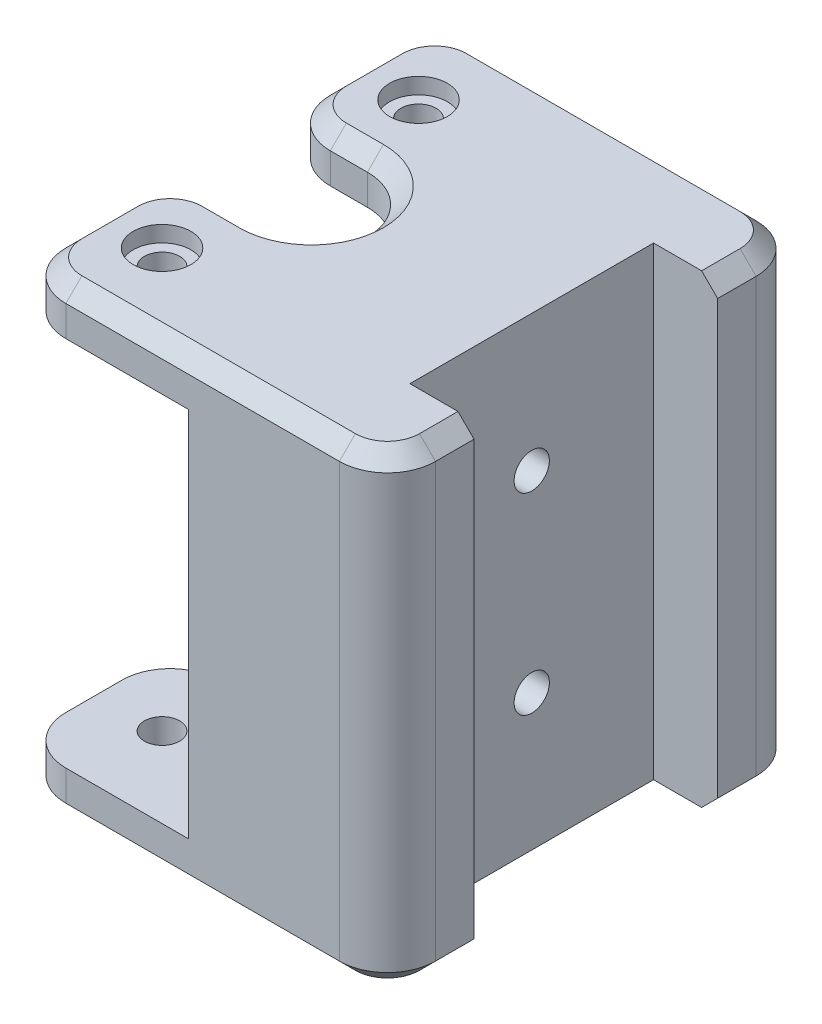
SolidWorks part; units mm, degrees
ref_plane "Спереди" through (0, 0, 0) normal (0, 0, 1) x (1, 0, 0)
ref_plane "Сверху" through (0, 0, 0) normal (0, 1, 0) x (1, 0, 0)
ref_plane "Справа" through (0, 0, 0) normal (1, 0, 0) x (0, 0, -1)
sketch "Эскиз2" plane through (0, 0, 0) normal (0, 1, 0) x (1, 0, 0)
  line L0 (23.6854, 8) -> (23.6854, -8) construction
  line L2 (19.6854, 13) -> (42.75, 13)
  line L3 (19.6854, 13) -> (19.6854, -13)
  line L4 (19.6854, -13) -> (42.75, -13)
  line L5 (42.75, 13) -> (42.75, -13)
  line L6 (19.6854, 13) -> (42.75, -13) construction
  line L7 (19.6854, -13) -> (42.75, 13) construction
  circle A0 centre (0, 0) radius 25 construction
  circle A1 centre (23.6854, 8) radius 1.1
  circle A2 centre (23.6854, -8) radius 1.1
  point P7 (31.2177, 0)
  dimension "D1" = 50
  dimension "D3" = 2.2
  dimension "D4" = 2.2
  dimension "D2" = 16
  dimension "D5" = 4
  dimension "D6" = 42.75
  dimension "D7" = 26
extrude "Бобышка-Вытянуть1" add sketch "Эскиз2" along normal mid plane 29
sketch "Эскиз3" plane through (0, 0, 0) normal (0, 1, 0) x (1, 0, 0)
  circle A0 centre (0, 0) radius 33
  dimension "D1" = 66
extrude "Вырез-Вытянуть1" cut sketch "Эскиз3" against normal mid plane 23.2
sketch "Эскиз4" plane through (0, 14.5, 0) normal (0, 1, 0) x (1, 0, 0)
  line L0 (25, 3.5) -> (19.6854, 3.5)
  line L1 (19.6854, 13) -> (19.6854, -13) construction
  line L2 (19.6854, 3.5) -> (19.6854, -3.5)
  line L3 (19.6854, -3.5) -> (25, -3.5)
  circle A0 centre (0, 0) radius 25 construction
  circle A1 centre (25, 0) radius 3.5
  line M6 (19.6854, 13) -> (19.6854, -13)
  dimension "D1" = 7
extrude "Вырез-Вытянуть2" cut sketch "Эскиз4" against normal through all contours A1 | A1 L0 L3 M6
sketch "Эскиз5" plane through (42.75, 0, 0) normal (1, 0, 0) x (0, 0, -1)
  line L0 (-13, -14.5) -> (13, -14.5) construction
  line L1 (-7.6, 14.5) -> (7.6, 14.5)
  line L2 (-7.6, 14.5) -> (-7.6, -14.5)
  line L3 (-7.6, -14.5) -> (7.6, -14.5)
  line L4 (7.6, 14.5) -> (7.6, -14.5)
  line L5 (-7.6, 14.5) -> (7.6, -14.5) construction
  line L6 (-7.6, -14.5) -> (7.6, 14.5) construction
  point P0 (0, 0)
  dimension "D1" = 15.2
extrude "Вырез-Вытянуть3" cut sketch "Эскиз5" against normal blind 4
fillet "Скругление1" radius 3 10 edges at (42.75, 0, -13) (19.6854, -13.05, -13) (19.6854, -13.05, -3.5) (19.6854, -13.05, 3.5) (19.6854, -13.05, 13) (19.6854, 13.05, -13) (19.6854, 13.05, -3.5) (19.6854, 13.05, 3.5) (19.6854, 13.05, 13) (42.75, 0, 13)
sketch "Эскиз6" plane through (38.75, 0, 0) normal (1, 0, 0) x (0, 0, -1)
  line L0 (-7.6, 0) -> (7.6, 0) construction
  line L1 (-7.6, 14.5) -> (-7.6, -14.5) construction
  line L2 (7.6, -14.5) -> (7.6, 14.5) construction
  circle A0 centre (0, 6) radius 1.1
  circle A1 centre (0, -6) radius 1.1
  point P12 (0, 0)
  dimension "D2" = 2.2
  dimension "D1" = 12
extrude "Вырез-Вытянуть4" cut sketch "Эскиз6" against normal through all
chamfer "Фаска1" distance 1 angle 45 30 edges at (42.75, -14.5, -8.8) (41.8713, -14.5, -12.1213) (31.2177, -14.5, -13) (20.5641, -14.5, -12.1213) (19.6854, -14.5, -8.25) (20.5641, -14.5, -4.3787) (23.8427, -14.5, -3.5) (28.5, -14.5, 0) (23.8427, -14.5, 3.5) (20.5641, -14.5, 4.3787) (19.6854, -14.5, 8.25) (42.75, -14.5, 8.8) (20.5641, -14.5, 12.1213) (41.8713, -14.5, 12.1213) (31.2177, -14.5, 13) (42.75, 14.5, -8.8) (41.8713, 14.5, -12.1213) (31.2177, 14.5, -13) (20.5641, 14.5, -12.1213) (19.6854, 14.5, -8.25) (20.5641, 14.5, -4.3787) (23.8427, 14.5, -3.5) (28.5, 14.5, 0) (23.8427, 14.5, 3.5) (20.5641, 14.5, 4.3787) (19.6854, 14.5, 8.25) (42.75, 14.5, 8.8) (20.5641, 14.5, 12.1213) (41.8713, 14.5, 12.1213) (31.2177, 14.5, 13)
sketch "Эскиз7" plane through (0, 14.5, 0) normal (0, 1, 0) x (1, 0, 0)
  circle A0 centre (23.6854, 8) radius 1.8
  circle A1 centre (23.6854, -8) radius 1.8
  dimension "D1" = 3.6
  dimension "D2" = 3.6
extrude "Вырез-Вытянуть5" cut sketch "Эскиз7" against normal blind 1
mirror "Зеркальное отражение1" about plane through (0, 0, 0) normal (0, 1, 0) of "Вырез-Вытянуть5"
sketch "Эскиз8" plane through (0, 0, 0) normal (1, 0, 0) x (0, 0, -1)
  line L1 (1.1258, 4.05) -> (2.2517, 6)
  line L2 (2.2517, 6) -> (1.1258, 7.95)
  line L3 (1.1258, 7.95) -> (-1.1258, 7.95)
  line L4 (-1.1258, 7.95) -> (-2.2517, 6)
  line L5 (-2.2517, 6) -> (-1.1258, 4.05)
  line L6 (-1.1258, 4.05) -> (1.1258, 4.05)
  line L7 (1.1258, -7.95) -> (2.2517, -6)
  line L8 (2.2517, -6) -> (1.1258, -4.05)
  line L9 (1.1258, -4.05) -> (-1.1258, -4.05)
  line L10 (-1.1258, -4.05) -> (-2.2517, -6)
  line L11 (-2.2517, -6) -> (-1.1258, -7.95)
  line L12 (-1.1258, -7.95) -> (1.1258, -7.95)
  circle A0 centre (0, 6) radius 1.95 construction
  circle A1 centre (0, -6) radius 1.95 construction
  dimension "D1" = 3.9
  dimension "D2" = 3.9
extrude "Вырез-Вытянуть6" cut sketch "Эскиз8" along normal offset from surface (35.75 mm away) 3 up to face at (38.75, 6, -1.1)
equation "\"motor_diameter\"= 30"
equation "\"mm_diameter\"= IIF ( \"motor_diameter\" < 34 , 41 , \"motor_diameter\" + 8 )"
equation "\"upper_shafts_diameter\"= 5"
equation "\"upper_shats_length\"= 180"
equation "\"upper_bearing_d1\"= 10"
equation "\"upper_bearing_d2\"= 5"
equation "\"upper_bearing_h\"= 15"
equation "\"lower_shafts_diameter\"= 5"
equation "\"lower_shafts_length\"= 180"
equation "\"lower_bearing_d1\"= 10"
equation "\"lower_bearing_d2\"= 5"
equation "\"lower_bearing_h\"= 15"
equation "\"print_offset\"= 0.2"
equation "\"bh_screws_d\"= 2"
equation "\"bh_screws_h\"= 20"
equation "\"bh_screws_hh_d\"= 3.4"
equation "\"bh_screws_hh_h\"= 2"
equation "\"bh_nut_d\"= 3.8"
equation "\"bh_nut_h\"= 2"
equation "\"motor_screws_d\"= 3"
equation "\"motor_screws_h\"= 16"
equation "\"motor_screws_hh_d\"= 5.5"
equation "\"motor_screws_hh_h\"= 3"
equation "\"plate_hole_distance\"= 25.4"
equation "\"plate_screws_d\"= 6.5"
equation "\"shafts_diameter\"= IIF ( \"mm_diameter\" < 42 , 42 + 8 , \"mm_diameter\" + 8 )"
equation "\"central_hole_diameter\"= 8"
equation "\"bh_thikness\"= 4"
equation "\"ends_screws_d\"= 4"
equation "\"ends_screws_h\"= 16"
equation "\"ends_screws_hh_d\"= 6.7"
equation "\"ends_screws_hh_h\"= 4.1"
equation "\"ends_nut_d\"= 6.8"
equation "\"ends_nut_h\"= 3"
equation "\"system_radius\" = ( \"shafts_diameter\" + 12 + \"bh_thikness\" / 2 ) / 2"
equation "\"encoder_distance\"= \"system_radius\" + 4"
equation "\"tape_position\"= \"encoder_distance\" - 2 + 3.9 + 1.7 / 2"
equation "\"D1@Эскиз2\"=\"shafts_diameter\""
equation "\"D3@Эскиз2\"=\"bh_screws_d\"+\"print_offset\""
equation "\"D4@Эскиз2\"=\"D3@Эскиз2\""
equation "\"D5@Эскиз2\"=\"bh_thikness\""
equation "\"D6@Эскиз2\"=\"tape_position\"+4"
equation "\"D1@Бобышка-Вытянуть1\"=\"lower_bearing_h\"+\"bh_thikness\"*2+6"
equation "\"D1@Эскиз3\"=\"system_radius\"*2+2"
equation "\"D1@Вырез-Вытянуть1\"=\"lower_bearing_h\"+\"bh_thikness\"*2+\"print_offset\""
equation "\"D1@Эскиз4\"=\"lower_shafts_diameter\"+2"
equation "\"D1@Эскиз5\"=\"print_offset\"+15"
equation "\"D2@Эскиз6\"=\"bh_screws_d\"+\"print_offset\""
equation "\"D1@Эскиз7\"=\"bh_screws_hh_d\"+\"print_offset\""
equation "\"D2@Эскиз7\"=\"D1@Эскиз7\""
equation "\"D1@Эскиз8\"=\"bh_nut_d\"+\"print_offset\"/2"
equation "\"D2@Эскиз8\"=\"D1@Эскиз8\""
equation "\"ft_sensor_d1\" = 9.8"
equation "\"ft_sensor_d2\"= 24.9"
equation "\"ft_sensor_h\"= 7"
equation "\"carbon_pipe_d\"= 14"
